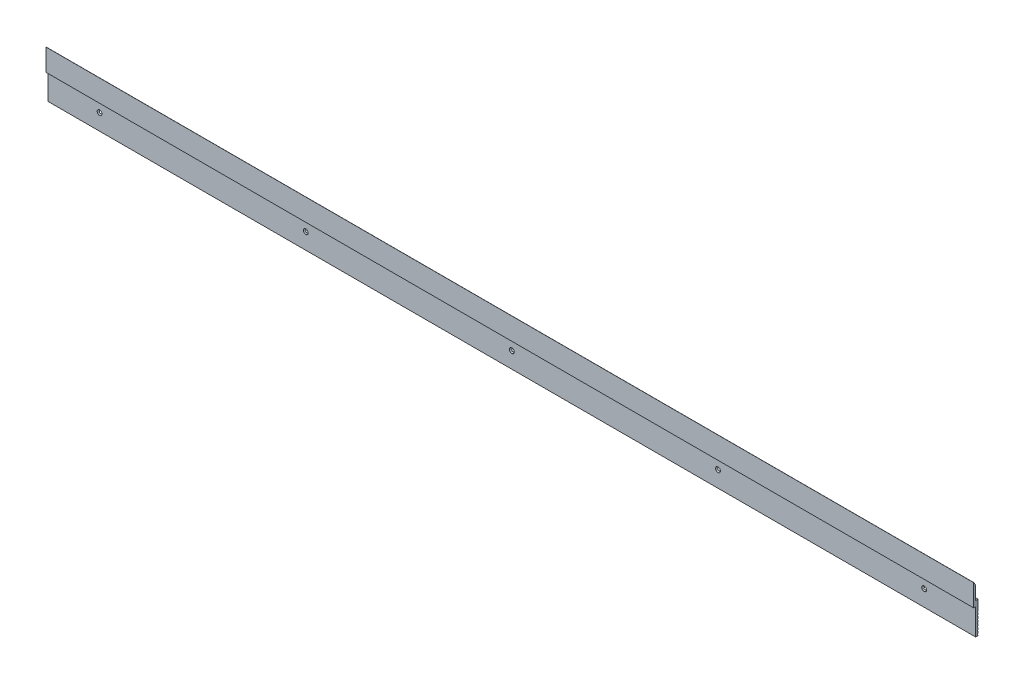
SolidWorks part; units mm, degrees
ref_plane "Front" through (0, 0, 0) normal (0, 0, 1) x (1, 0, 0)
ref_plane "Top" through (0, 0, 0) normal (0, 1, 0) x (1, 0, 0)
ref_plane "Right" through (0, 0, 0) normal (1, 0, 0) x (0, 0, -1)
sketch "Sketch1" plane through (0, 0, 0) normal (1, 0, 0) x (0, 0, -1)
  line L0 (0, -5.334) -> (0, 16.256)
  line L1 (0, 0) -> (0, -31.242) construction
  dimension "D1" = 21.59
  dimension "D2" = 31.242
  dimension "D3" = 47.498
extrude "Extrude-Thin1" add sketch "Sketch1" along normal mid plane 914.4 thin thin type one direction reverse wall 2.032
sketch "Sketch2" plane through (0, 0, 0) normal (1, 0, 0) x (0, 0, -1)
  line L0 (0, 0) -> (0, -31.242) construction
  line L1 (0, 0) -> (0, -31.242)
extrude "Extrude-Thin2" add sketch "Sketch2" along normal mid plane 914.4 thin thin type one direction reverse wall 2.286
chamfer "Chamfer1" distance 3.302 angle 30 1 edges at (0, 16.256, 0)
sketch "Sketch3" plane through (0, 0, -2.286) normal (0, 0, -1) x (-1, 0, 0)
  line L0 (-457.2, -31.242) -> (457.2, -31.242) construction
  line L2 (0, -15.367) -> (0, 0) construction
  circle A2 centre (0, -15.367) radius 2.3876
  dimension "D1" = 4.7752
  dimension "D2" = 15.875
extrude "Cut-Extrude1" cut sketch "Sketch3" against normal up to surface (2.286 mm away) up to face at (114.3, -11.811, 0)
pattern_linear "LPattern2" count 5 spacing 203.2 along (-1, 0, 0) count 5 spacing 203.2 along (1, 0, 0) of "Cut-Extrude1"
sketch "Sketch4" plane through (457.2, 0, 0) normal (1, 0, 0) x (0, 0, -1)
  line L0 (2.286, 0) -> (2.286, -31.242) construction
  line L1 (2.286, -31.242) -> (0, -31.242) construction
  circle A0 centre (2.286, -29.972) radius 0.635
  dimension "D1" = 1.27
  dimension "D2" = 1.27
extrude "Cut-Extrude2" cut sketch "Sketch4" against normal through all
pattern_linear "LPattern1" count 7 spacing 3.175 along (0, 1, 0) of "Cut-Extrude2"
